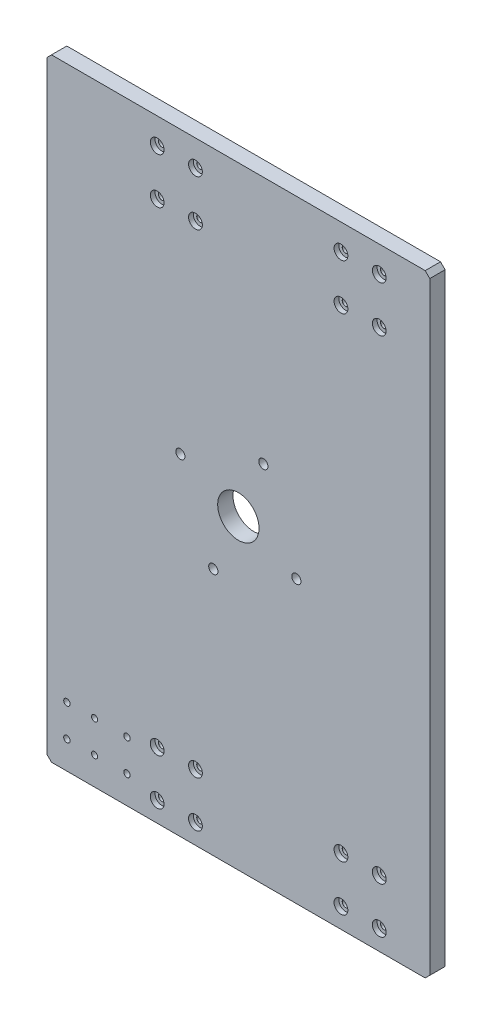
SolidWorks part; units mm, degrees
ref_plane "Plan de face" through (0, 0, 0) normal (0, 0, 1) x (1, 0, 0)
ref_plane "Plan de dessus" through (0, 0, 0) normal (0, 1, 0) x (1, 0, 0)
ref_plane "Plan de droite" through (0, 0, 0) normal (1, 0, 0) x (0, 0, -1)
sketch "Esquisse1" plane through (0, 0, 0) normal (0, 0, 1) x (1, 0, 0)
  line L1 (-125, -200) -> (125, -200)
  line L2 (-125, -200) -> (-125, 200)
  line L3 (-125, 200) -> (125, 200)
  line L4 (125, -200) -> (125, 200)
  line L5 (-125, -200) -> (125, 200) construction
  line L6 (-125, 200) -> (125, -200) construction
  point P0 (0, 0)
  dimension "D1" = 400
  dimension "D2" = 250
extrude "Boss.-Extru.1" add sketch "Esquisse1" along normal blind 10
ref_plane "Plan1" through (0, 0, 0) normal (1, 0, 0) x (0, 0, -1)
ref_plane "Plan2" through (0, 0, 0) normal (0, 1, 0) x (1, 0, 0)
sketch "Esquisse2" plane through (0, 0, 0) normal (0, 0, -1) x (-1, 0, 0)
  circle A0 centre (0, 0) radius 13.5
  dimension "D1" = 27
extrude "Enlèv. mat.-Extru.1" cut sketch "Esquisse2" against normal through all
chamfer "Chanfrein1" distance 3 angle 45 4 edges at (-125, -200, 5) (125, -200, 5) (125, 200, 5) (-125, 200, 5)
hole_wizard "Trou taraudé M51" positions "Esquisse6" profile "Esquisse5" tap size "M5" standard "ISO" end condition through all
sketch "Esquisse6" plane through (0, 0, 10) normal (0, 0, 1) x (1, 0, 0)
  point P0 (-72.6985, -161.0797)
  point P3 (-72.6985, -181.8387)
  point P6 (-111.9372, -181.8387)
  point P9 (-111.9372, -161.0797)
sketch "Esquisse5" plane through (-72.6985, -161.0797, 10) normal (1, 0, 0) x (0, -1, 0)
  line L0 (0, 0) -> (0, 10)
  line L1 (0, 10) -> (2.1, 10)
  line L2 (2.1, 10) -> (2.1, 0)
  line L5 (2.1, 0) -> (0, 0)
  line L11 (0, -6.35) -> (0, 107.95) construction
  dimension "Diamètre du trou pour taraudage jusqu'au prochain" = 4.2
  dimension "Profondeur du trou pour taraudage jusqu'au prochain" = 10
cosmetic thread "Filetage de perçage3" parameters "D2"=5
cosmetic thread "Filetage de perçage4" parameters "D2"=5
cosmetic thread "Filetage de perçage5" parameters "D2"=5
cosmetic thread "Filetage de perçage6" parameters "D2"=5
hole_wizard "Trous de centrage Ø4.0mm2" positions "Esquisse9" profile "Esquisse8" hole size "Ø4.0" standard "ISO" end condition through all
sketch "Esquisse9" plane through (0, 0, 10) normal (0, 0, 1) x (1, 0, 0)
  point P0 (-93.8631, -161.0797)
  point P3 (-93.8631, -181.8387)
sketch "Esquisse8" plane through (-93.8631, -161.0797, 10) normal (1, 0, 0) x (0, -1, 0)
  line L0 (0, 0) -> (0, 10)
  line L1 (0, 10) -> (2, 10)
  line L2 (2, 10) -> (2, 0)
  line L5 (2, 0) -> (0, 0)
  line L11 (0, -6.35) -> (0, 107.95) construction
  dimension "Diamètre du perçage jusqu'au prochain" = 4
  dimension "Profondeur du perçage jusqu'au prochain" = 10
sketch "Esquisse10" plane through (0, 0, 10) normal (0, 0, 1) x (1, 0, 0)
  circle A0 centre (0, 0) radius 41.25 construction
  dimension "D1" = 82.5
hole_wizard "Trous de centrage Ø6.0mm2" positions "Esquisse26" profile "Esquisse25" hole size "Ø6.0" standard "ISO" end condition through all
sketch "Esquisse26" plane through (0, 0, 10) normal (0, 0, 1) x (1, 0, 0)
  point P0 (16.3571, 37.8683)
  point P2 (37.8683, -16.3571)
  point P4 (-16.3571, -37.8683)
  point P6 (-37.8683, 16.3571)
sketch "Esquisse25" plane through (16.3571, 37.8683, 10) normal (1, 0, 0) x (0, -1, 0)
  line L0 (0, 0) -> (0, 10)
  line L1 (0, 10) -> (3, 10)
  line L2 (3, 10) -> (3, 0)
  line L5 (3, 0) -> (0, 0)
  line L11 (0, -6.35) -> (0, 107.95) construction
  dimension "Diamètre du perçage jusqu'au prochain" = 6
  dimension "Profondeur du perçage jusqu'au prochain" = 10
hole_wizard "Dégagement M41" positions "Esquisse28" profile "Esquisse27" hole size "M4" standard "JIS" end condition through all
sketch "Esquisse28" plane through (0, 0, 0) normal (0, 0, -1) x (-1, 0, 0)
  point P0 (28, -187)
  point P2 (28, -157)
  point P4 (53, -157)
  point P6 (53, -187)
sketch "Esquisse27" plane through (-28, -187, 0) normal (1, 0, 0) x (0, 1, 0)
  line L0 (0, 0) -> (0, 10)
  line L1 (0, 10) -> (2.25, 10)
  line L2 (2.25, 10) -> (2.25, 0)
  line L5 (2.25, 0) -> (0, 0)
  line L11 (0, -6.35) -> (0, 107.95) construction
  dimension "Diamètre du perçage jusqu'au prochain" = 4.5
  dimension "Profondeur du perçage jusqu'au prochain" = 10
pattern_linear "Répétition linéaire1" count 2 spacing 120 along (1, 0, 0) count 2 spacing 340 along (0, 1, 0) of "Dégagement M41"
hole_wizard "Chambrage pour vis à tête ronde bombée M41" positions "Esquisse30" profile "Esquisse29" counterbore size "M4" standard "Ansi Metric" end condition through all
sketch "Esquisse30" plane through (0, 0, 10) normal (0, 0, 1) x (1, 0, 0)
  point P0 (92, -157)
sketch "Esquisse29" plane through (92, -157, 10) normal (1, 0, 0) x (0, -1, 0)
  line L0 (0, 0) -> (0, 10)
  line L1 (0, 10) -> (2.25, 10)
  line L2 (2.25, 3.125) -> (2.25, 10)
  line L3 (2.25, 3.125) -> (2.275, 3.1)
  line L4 (2.275, 3.1) -> (4.5, 3.1)
  line L5 (4.5, 3.1) -> (4.5, 0)
  line L7 (0, 0) -> (4.5, 0)
  line L9 (-2.25, 3.125) -> (-2.275, 3.1) construction
  line L11 (0, -6.35) -> (0, 107.95) construction
  dimension "Diamètre du perçage jusqu'au prochain" = 4.5
  dimension "Profondeur du perçage jusqu'au prochain" = 10
  dimension "Diamètre du chambrage" = 9
  dimension "Profondeur du chambrage" = 3.1
  dimension "Diamètre du fraisage milieu" = 4.55
  dimension "Angle du fraisage milieu" = 90
pattern_linear "Répétition linéaire2" count 2 spacing 30 along (0, -1, 0) count 2 spacing 25 along (-1, 0, 0) of "Chambrage pour vis à tête ronde bombée M41"
pattern_linear "Répétition linéaire3" count 2 spacing 120 along (-1, 0, 0) count 2 spacing 340 along (0, 1, 0) of "Répétition linéaire2", "Chambrage pour vis à tête ronde bombée M41"
